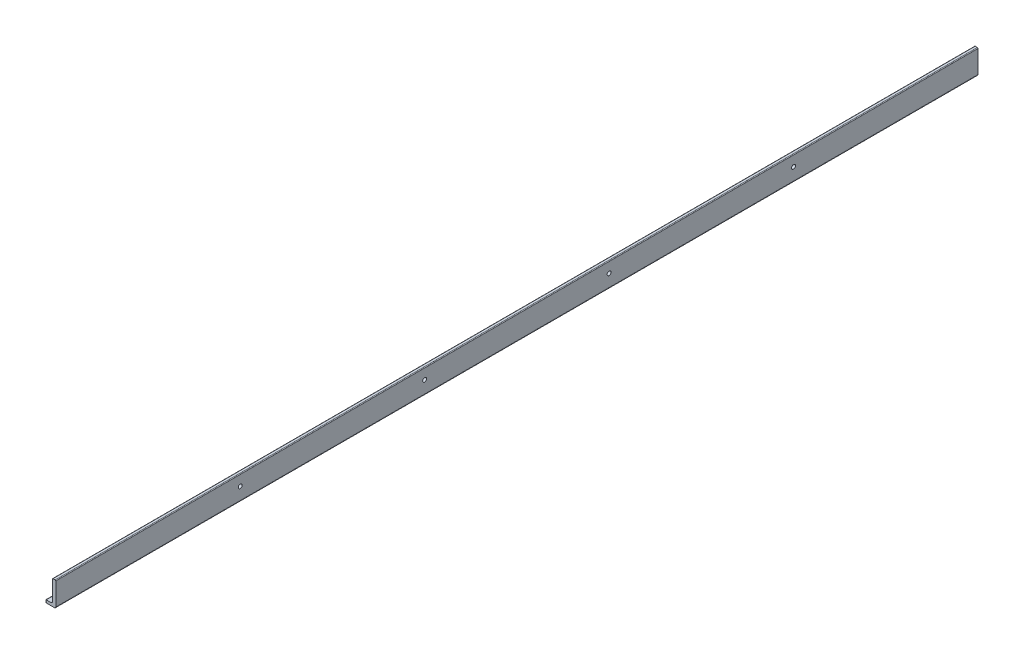
SolidWorks part; units mm, degrees
material "1.4511 (X3CrNb17)"
ref_plane "前视基准面" through (0, 0, 0) normal (0, 0, 1) x (1, 0, 0)
ref_plane "上视基准面" through (0, 0, 0) normal (0, 1, 0) x (1, 0, 0)
ref_plane "右视基准面" through (0, 0, 0) normal (1, 0, 0) x (0, 0, -1)
sketch "草图1" plane through (0, 0, 0) normal (0, 0, 1) x (1, 0, 0)
  line L0 (0, 0) -> (0, 18)
  line L1 (0, 18) -> (-2.5, 18)
  line L2 (-2.5, 18) -> (-2.5, 2)
  line L3 (-2.5, 2) -> (-7.5, 2)
  line L4 (-7.5, 2) -> (-7.5, 0)
  line L5 (-7.5, 0) -> (0, 0)
  dimension "D1" = 18
  dimension "D2" = 2.5
  dimension "D3" = 16
  dimension "D4" = 5
extrude "凸台-拉伸1" add sketch "草图1" along normal blind 680
sketch "草图2" plane through (-2.5, 0, 0) normal (-1, 0, 0) x (0, 0, 1)
  line L0 (680, 18) -> (0, 18) construction
  line L1 (0, 18) -> (0, 2) construction
  point P0 (136, 10)
  point P7 (272, 10)
  point P8 (408, 10)
  point P9 (544, 10)
  dimension "D1" = 8
  dimension "D2" = 136
  dimension "D3" = 4
hole_wizard "M3.5 螺纹孔1" positions "草图3" profile "草图5" tap size "M3.5" standard "GB" end condition through all
sketch "草图3" plane through (-2.5, 0, 0) normal (-1, 0, 0) x (0, 0, 1)
  point P0 (136, 10)
  point P3 (272, 10)
  point P6 (408, 10)
  point P9 (544, 10)
sketch "草图5" plane through (-2.5, 10, 136) normal (0, 1, 0) x (0, 0, 1)
  line L0 (0, 0) -> (0, 2.5)
  line L1 (0, 2.5) -> (1.45, 2.5)
  line L2 (1.45, 2.5) -> (1.45, 0)
  line L5 (1.45, 0) -> (0, 0)
  line L11 (0, -6.35) -> (0, 107.95) construction
  dimension "通孔螺纹孔钻头直径" = 2.9
  dimension "通孔螺纹孔钻头深度" = 2.5
cosmetic thread "孔螺蚊线1" parameters "D2"=3.5
cosmetic thread "孔螺蚊线2" parameters "D2"=3.5
cosmetic thread "孔螺蚊线3" parameters "D2"=3.5
cosmetic thread "孔螺蚊线4" parameters "D2"=3.5
fillet "圆角1" radius 1 2 edges at (-2.5, 2, 340) (0, 0, 340)
fillet "圆角2" radius 0.5 6 edges at (-7.5, 2, 340) (-7.5, 1, 680) (-7.5, 0, 340) (-7.5, 1, 0) (-2.5, 18, 340) (0, 18, 340)
